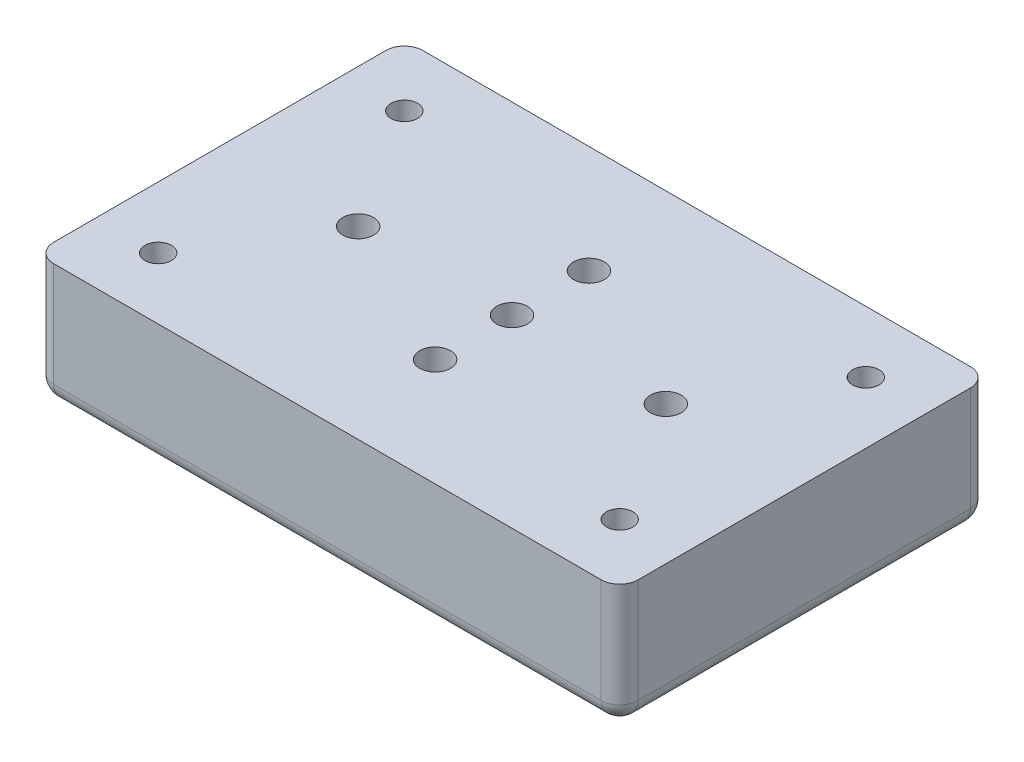
SolidWorks part; units mm, degrees
ref_plane "Front Plane" through (0, 0, 0) normal (0, 0, 1) x (1, 0, 0)
ref_plane "Top Plane" through (0, 0, 0) normal (0, 1, 0) x (1, 0, 0)
ref_plane "Right Plane" through (0, 0, 0) normal (1, 0, 0) x (0, 0, -1)
sketch "Sketch1" plane through (0, 0, 0) normal (0, 1, 0) x (1, 0, 0)
  line L1 (-102.5206, -50.7506) -> (-7.5206, -50.7506)
  line L2 (-102.5206, -50.7506) -> (-102.5206, -110.7506)
  line L3 (-102.5206, -110.7506) -> (-7.5206, -110.7506)
  line L4 (-7.5206, -50.7506) -> (-7.5206, -110.7506)
  dimension "D1" = 60
  dimension "D2" = 95
extrude "Boss-Extrude1" add sketch "Sketch1" along normal blind 20
hole_wizard "CBORE for M4 Cheese Head Screw1" positions "Sketch2" profile "Sketch4" counterbore size "M4" standard "AS" end condition through all
sketch "Sketch2" plane through (0, 0, 0) normal (0, -1, 0) x (-1, 0, 0)
  line L0 (7.5206, -50.7506) -> (102.5206, -50.7506) construction
  line L1 (102.5206, -110.7506) -> (7.5206, -110.7506) construction
  line L2 (102.5206, -50.7506) -> (102.5206, -110.7506) construction
  line L3 (7.5206, -110.7506) -> (7.5206, -50.7506) construction
  point P0 (17.5206, -60.7506)
  point P2 (92.5206, -60.7506)
  point P4 (92.5206, -100.7506)
  point P6 (17.5206, -100.7506)
  dimension "D1" = 10
  dimension "D2" = 10
  dimension "D3" = 10
  dimension "D4" = 10
sketch "Sketch4" plane through (-17.5206, 0, 60.7506) normal (1, 0, 0) x (0, 0, -1)
  line L0 (0, 0) -> (0, 20)
  line L1 (0, 20) -> (2.15, 20)
  line L3 (2.15, 20) -> (2.15, 4)
  line L4 (2.15, 4) -> (3.6, 4)
  line L5 (3.6, 4) -> (3.6, 0)
  line L7 (3.6, 0) -> (0, 0)
  line L11 (0, -6.35) -> (0, 107.95) construction
  dimension "Thru Hole Dia." = 4.3
  dimension "Thru Hole Depth" = 20
  dimension "C'Bore Dia." = 7.2
  dimension "C'Bore Depth" = 4
hole_wizard "Ø5.0mm Dowel Hole1" positions "Sketch5" profile "Sketch6" hole size "Ø5.0" standard "AS" end condition through all
sketch "Sketch5" plane through (0, 0, 0) normal (0, -1, 0) x (-1, 0, 0)
  line L0 (7.5206, -80.7506) -> (102.5206, -80.7506) construction
  line L1 (7.5206, -110.7506) -> (7.5206, -50.7506) construction
  line L2 (102.5206, -50.7506) -> (102.5206, -110.7506) construction
  point P0 (30.0206, -80.7506)
  point P2 (55.0206, -80.7506)
  point P4 (80.0206, -80.7506)
  point P28 (55.0206, -68.2506)
  point P30 (55.0206, -93.2506)
  point P33 (38.7742, -93.2506)
  point P34 (0, 0)
  point P35 (0, 0)
  dimension "D1" = 25
  dimension "D2" = 25
  dimension "D3" = 12.5
  dimension "D4" = 25
sketch "Sketch6" plane through (-30.0206, 0, 80.7506) normal (1, 0, 0) x (0, 0, -1)
  line L0 (0, 0) -> (0, 20)
  line L1 (0, 20) -> (2.5, 20)
  line L2 (2.5, 20) -> (2.5, 0)
  line L5 (2.5, 0) -> (0, 0)
  line L11 (0, -6.35) -> (0, 107.95) construction
  dimension "Thru Hole Dia." = 5
  dimension "Thru Hole Depth" = 20
fillet "Fillet1" radius 3 8 edges at (-7.5206, 10, 50.7506) (-102.5206, 10, 50.7506) (-7.5206, 10, 110.7506) (-102.5206, 10, 110.7506) (-55.0206, 0, 50.7506) (-7.5206, 0, 80.7506) (-55.0206, 0, 110.7506) (-102.5206, 0, 80.7506)
